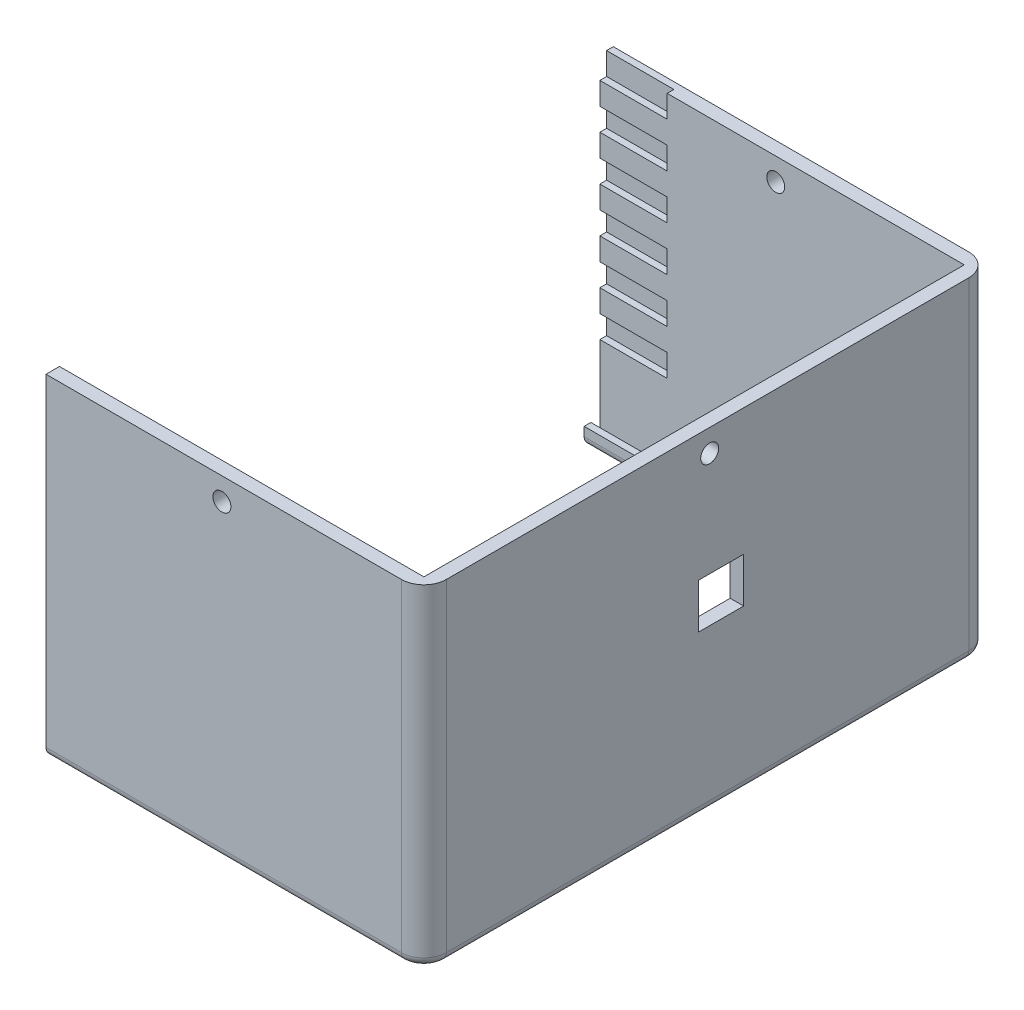
SolidWorks part; units mm, degrees
ref_plane "Front Plane" through (0, 0, 0) normal (0, 0, 1) x (1, 0, 0)
ref_plane "Top Plane" through (0, 0, 0) normal (0, 1, 0) x (1, 0, 0)
ref_plane "Right Plane" through (0, 0, 0) normal (1, 0, 0) x (0, 0, -1)
sketch "Sketch1" plane through (0, 0, 0) normal (0, 1, 0) x (1, 0, 0)
  line L0 (-76.7346, 32.1468) -> (-76.7346, 52.1468)
  line L2 (-76.7346, 32.1468) -> (-76.7346, -68.2432)
  line L3 (-76.7346, -68.2432) -> (60.5554, -68.2432)
  line L6 (-79.7346, 55.1468) -> (88.645, 55.1468)
  line L7 (-76.7346, 52.1468) -> (85.645, 52.1468)
  line L9 (85.645, 52.1468) -> (85.645, -68.2432)
  line L10 (85.645, -68.2432) -> (60.5554, -68.2432)
  line L11 (-79.7346, 55.1468) -> (-79.7346, -71.2432)
  line L12 (-79.7346, -71.2432) -> (88.645, -71.2432)
  line L13 (88.645, 55.1468) -> (88.645, -71.2432)
  dimension "D1" = 100.39
  dimension "D2" = 137.29
  dimension "D3" = 20
  dimension "D5" = 3
  dimension "D6" = 3
  dimension "D7" = 3
  dimension "D8" = 3
extrude "Boss-Extrude1" add sketch "Sketch1" along normal blind 70
sketch "Sketch2" plane through (0, 0, 0) normal (0, -1, 0) x (-1, 0, 0)
  line L1 (79.7346, -71.2432) -> (-88.645, -71.2432)
  line L2 (79.7346, -71.2432) -> (79.7346, 55.1468)
  line L3 (79.7346, 55.1468) -> (-88.645, 55.1468)
  line L4 (-88.645, -71.2432) -> (-88.645, 55.1468)
extrude "Boss-Extrude2" add sketch "Sketch2" along normal blind 4
sketch "Sketch3" plane through (0, 0, 0) normal (0, 1, 0) x (1, 0, 0)
  line L0 (85.645, -68.2432) -> (85.645, 52.1468) construction
  line L1 (81.145, -47.6932) -> (-61.6346, -47.6932)
  line L2 (81.145, -47.6932) -> (81.145, 48.6468)
  line L3 (81.145, 48.6468) -> (-61.6346, 48.6468)
  line L4 (-61.6346, -47.6932) -> (-61.6346, 48.6468)
  line L5 (85.645, 52.1468) -> (-76.7346, 52.1468) construction
  line L6 (-76.7346, -68.2432) -> (85.645, -68.2432) construction
  line L7 (-76.7346, 52.1468) -> (-76.7346, -68.2432) construction
  dimension "D1" = 4.5
  dimension "D2" = 3.5
  dimension "D3" = 20.55
  dimension "D4" = 15.1
extrude "Cut-Extrude1" cut sketch "Sketch3" against normal blind 4
fillet "Fillet1" radius 5 4 edges at (-79.7346, 33, 71.2432) (-79.7346, 33, -55.1468) (88.645, 33, -55.1468) (88.645, 33, 71.2432)
fillet "Fillet4" radius 2 8 edges at (87.1805, -4, -53.6823) (4.4552, -4, -55.1468) (-78.2701, -4, -53.6823) (-79.7346, -4, 8.0482) (-78.2701, -4, 69.7787) (4.4552, -4, 71.2432) (87.1805, -4, 69.7787) (88.645, -4, 8.0482)
fillet "Fillet5" radius 2 4 edges at (-61.6346, -4, -0.4768) (9.7552, -4, -48.6468) (81.145, -4, -0.4768) (9.7552, -4, 47.6932)
sketch "Sketch4" plane through (-79.7346, 0, 0) normal (-1, 0, 0) x (0, 0, 1)
  line L1 (0.0087, 41.7497) -> (10.0087, 41.7497)
  line L2 (0.0087, 41.7497) -> (0.0087, 31.7497)
  line L3 (0.0087, 31.7497) -> (10.0087, 31.7497)
  line L4 (10.0087, 41.7497) -> (10.0087, 31.7497)
  line L5 (0.0087, 41.7497) -> (10.0087, 31.7497) construction
  line L6 (0.0087, 31.7497) -> (10.0087, 41.7497) construction
  point P0 (5.0087, 36.7497)
  dimension "D1" = 10
extrude "Cut-Extrude2" cut sketch "Sketch4" against normal blind 195
sketch "Sketch6" plane through (88.645, 0, 0) normal (1, 0, 0) x (0, 0, -1)
  line L0 (-66.2432, 70) -> (50.1468, 70) construction
  circle A0 centre (-7.5756, 65) radius 2
  dimension "D1" = 5
extrude "Cut-Extrude3" cut sketch "Sketch6" against normal blind 195
sketch "Sketch8" plane through (0, 0, -55.1468) normal (0, 0, -1) x (-1, 0, 0)
  line L0 (-83.645, 70) -> (74.7346, 70) construction
  line L1 (-83.645, 70) -> (-83.645, -2) construction
  line L2 (74.7346, -2) -> (74.7346, 70) construction
  circle A0 centre (-43.645, 65) radius 2
  circle A1 centre (34.7346, 65) radius 2
  dimension "D3" = 40
  dimension "D1" = 5
  dimension "D2" = 5
  dimension "D4" = 40
extrude "Cut-Extrude4" cut sketch "Sketch8" against normal blind 195
sketch "Sketch9" plane through (0, 0, 71.2432) normal (0, 0, 1) x (1, 0, 0)
  line L0 (-74.7346, 70) -> (83.645, 70) construction
  line L1 (4.4552, 70) -> (-99.4951, 70)
  line L2 (4.4552, 70) -> (4.4552, -18.0102)
  line L3 (4.4552, -18.0102) -> (-99.4951, -18.0102)
  line L4 (-99.4951, 70) -> (-99.4951, -18.0102)
extrude "Cut-Extrude5" cut sketch "Sketch9" against normal blind 201
sketch "Sketch10" plane through (4.4552, 0, 0) normal (-1, 0, 0) x (0, 0, 1)
  line L0 (47.6932, 0) -> (68.2432, 0) construction
  line L1 (52.6932, 0) -> (57.6932, 0)
  line L2 (52.6932, 0) -> (52.6932, -2)
  line L3 (52.6932, -2) -> (57.6932, -2)
  line L4 (57.6932, 0) -> (57.6932, -2)
  line L5 (47.6932, -2) -> (47.6932, 0) construction
  line L7 (62.6932, 0) -> (67.6932, 0)
  line L8 (62.6932, 0) -> (62.6932, -2)
  line L9 (62.6932, -2) -> (67.6932, -2)
  line L10 (67.6932, 0) -> (67.6932, -2)
  line L11 (-52.1468, 0) -> (-50.1468, 0)
  line L12 (-52.1468, 0) -> (-52.1468, -2)
  line L13 (-52.1468, -2) -> (-50.1468, -2)
  line L14 (-50.1468, 0) -> (-50.1468, -2)
  dimension "D1" = 5
  dimension "D2" = 5
  dimension "D3" = 2
  dimension "D4" = 5
  dimension "D5" = 5
  dimension "D6" = 2
extrude "Cut-Extrude6" cut sketch "Sketch10" against normal blind 15
sketch "Sketch11" plane through (4.4552, 0, 0) normal (-1, 0, 0) x (0, 0, 1)
  line L0 (68.2432, 70) -> (68.2432, 0) construction
  line L1 (68.2432, 65) -> (69.7432, 65)
  line L2 (68.2432, 65) -> (68.2432, 60)
  line L3 (68.2432, 60) -> (69.7432, 60)
  line L4 (69.7432, 65) -> (69.7432, 60)
  line L5 (68.2432, 70) -> (71.2432, 70) construction
  line L6 (68.2432, 55) -> (69.7432, 55)
  line L7 (68.2432, 55) -> (68.2432, 50)
  line L8 (68.2432, 50) -> (69.7432, 50)
  line L9 (69.7432, 55) -> (69.7432, 50)
  line L10 (68.2432, 45) -> (69.7432, 45)
  line L11 (68.2432, 45) -> (68.2432, 40)
  line L12 (68.2432, 40) -> (69.7432, 40)
  line L13 (69.7432, 45) -> (69.7432, 40)
  line L14 (68.2432, 35) -> (69.7432, 35)
  line L15 (68.2432, 35) -> (68.2432, 30)
  line L16 (68.2432, 30) -> (69.7432, 30)
  line L17 (69.7432, 35) -> (69.7432, 30)
  line L18 (68.2432, 25) -> (69.7432, 25)
  line L19 (68.2432, 25) -> (68.2432, 20)
  line L20 (68.2432, 20) -> (69.7432, 20)
  line L21 (69.7432, 25) -> (69.7432, 20)
  line L22 (68.2432, 15) -> (69.7432, 15)
  line L23 (68.2432, 15) -> (68.2432, 10)
  line L24 (68.2432, 10) -> (69.7432, 10)
  line L25 (69.7432, 15) -> (69.7432, 10)
  dimension "D1" = 1.5
  dimension "D2" = 5
  dimension "D3" = 5
  dimension "D4" = 6
extrude "Cut-Extrude7" cut sketch "Sketch11" against normal blind 15
sketch "Sketch12" plane through (4.4552, 0, 0) normal (-1, 0, 0) x (0, 0, 1)
  line L0 (-53.6468, 60) -> (-53.6468, 55)
  line L1 (-52.1468, 70) -> (-53.6468, 70)
  line L2 (-52.1468, 70) -> (-52.1468, 65)
  line L3 (-52.1468, 65) -> (-53.6468, 65)
  line L4 (-53.6468, 70) -> (-53.6468, 65)
  line L5 (-52.1468, 55) -> (-53.6468, 55)
  line L6 (-52.1468, 60) -> (-52.1468, 55)
  line L7 (-52.1468, 60) -> (-53.6468, 60)
  line L8 (-53.6468, 50) -> (-53.6468, 45)
  line L9 (-52.1468, 45) -> (-53.6468, 45)
  line L10 (-52.1468, 50) -> (-52.1468, 45)
  line L11 (-52.1468, 50) -> (-53.6468, 50)
  line L12 (-53.6468, 40) -> (-53.6468, 35)
  line L13 (-52.1468, 35) -> (-53.6468, 35)
  line L14 (-52.1468, 40) -> (-52.1468, 35)
  line L15 (-52.1468, 40) -> (-53.6468, 40)
  line L16 (-53.6468, 30) -> (-53.6468, 25)
  line L17 (-52.1468, 25) -> (-53.6468, 25)
  line L18 (-52.1468, 30) -> (-52.1468, 25)
  line L19 (-52.1468, 30) -> (-53.6468, 30)
  line L20 (-53.6468, 20) -> (-53.6468, 15)
  line L21 (-52.1468, 15) -> (-53.6468, 15)
  line L22 (-52.1468, 20) -> (-52.1468, 15)
  line L23 (-52.1468, 20) -> (-53.6468, 20)
  dimension "D1" = 1.5
  dimension "D2" = 5
  dimension "D3" = 6
extrude "Cut-Extrude8" cut sketch "Sketch12" against normal blind 15
